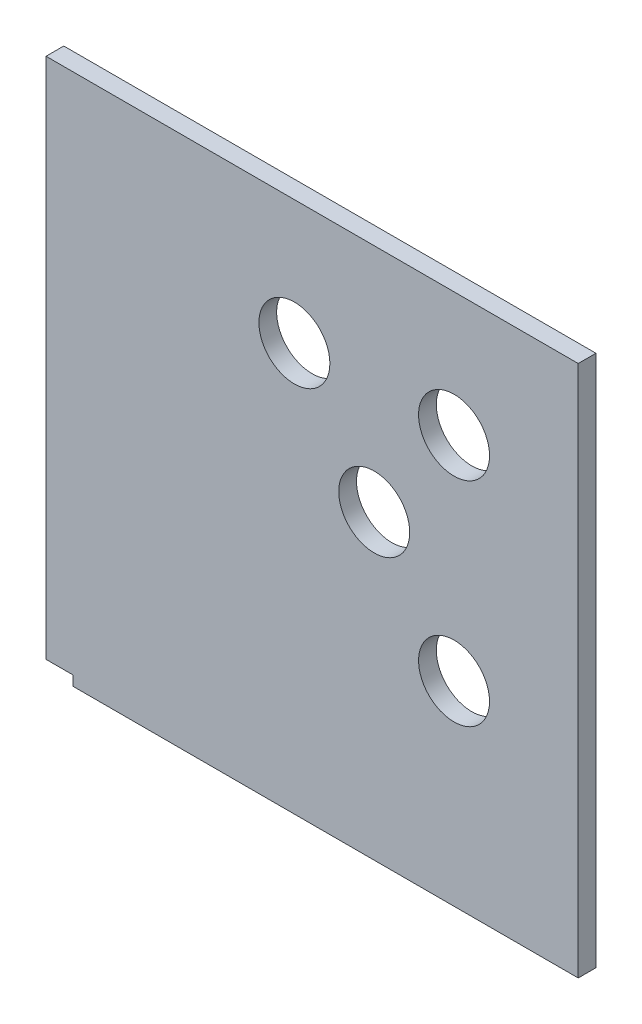
SolidWorks part; units mm, degrees
ref_plane "前视基准面" through (0, 0, 0) normal (0, 0, 1) x (1, 0, 0)
ref_plane "上视基准面" through (0, 0, 0) normal (0, 1, 0) x (1, 0, 0)
ref_plane "右视基准面" through (0, 0, 0) normal (1, 0, 0) x (0, 0, -1)
other "Configuration Table"
sketch "草图1" plane through (0, 0, 0) normal (0, 0, 1) x (1, 0, 0)
  line L1 (-150, -150) -> (150, -150)
  line L2 (-150, -150) -> (-150, 150)
  line L3 (-150, 150) -> (150, 150)
  line L4 (150, -150) -> (150, 150)
  line L5 (-150, -150) -> (150, 150) construction
  line L6 (-150, 150) -> (150, -150) construction
  point P0 (0, 0)
  dimension "D1" = 300
  dimension "D2" = 300
extrude "凸台-拉伸1" add sketch "草图1" along normal blind 10
sketch "草图2" plane through (0, 0, 10) normal (0, 0, 1) x (1, 0, 0)
  line L0 (-150, 150) -> (-150, -150) construction
  line L1 (-150, -150) -> (150, -150) construction
  circle A0 centre (-70, -70) radius 20
  circle A3 centre (35, 20) radius 20
  dimension "D3" = 40
  dimension "D4" = 90
  dimension "D10" = 40
  dimension "D1" = 80
  dimension "D2" = 80
  dimension "D5" = 105
extrude "切除-拉伸1" cut sketch "草图2" against normal through all contours A3
sketch "草图3" plane through (0, 0, 0) normal (0, 0, 1) x (1, 0, 0)
  line L4 (80, 80) -> (-10, 80) construction
  line L6 (-10, 80) -> (80, -40) construction
  circle A4 centre (80, 80) radius 20
  circle A5 centre (80, -40) radius 20
  circle A6 centre (-10, 80) radius 20
  circle A8 centre (35, 20) radius 20 construction
  circle A9 centre (35, 20) radius 20 construction
  point P6 (35, 20)
  dimension "D3" = 40
  dimension "D4" = 90
  dimension "D2" = 40
  dimension "D5" = 40
  dimension "D1" = 120
extrude "切除-拉伸2" cut sketch "草图3" along normal blind 10
sketch "草图4" plane through (0, 0, 10) normal (0, 0, 1) x (1, 0, 0)
  line L1 (-170.0688, -119.9497) -> (-134.6812, -119.9497)
  line L2 (-170.0688, -119.9497) -> (-170.0688, -155.3003)
  line L3 (-170.0688, -155.3003) -> (-134.6812, -155.3003)
  line L4 (-134.6812, -119.9497) -> (-134.6812, -155.3003)
  line L5 (-170.0688, -119.9497) -> (-134.6812, -155.3003) construction
  line L6 (-170.0688, -155.3003) -> (-134.6812, -119.9497) construction
  point P0 (-152.375, -137.625)
extrude "切除-拉伸3" cut sketch "草图4" against normal blind 25
sketch "草图5" plane through (0, -119.9497, 0) normal (0, -1, 0) x (1, 0, 0)
  line L4 (-150, 0) -> (-134.6812, 0)
  line L5 (-134.6812, 0) -> (-134.6812, 10)
  line L6 (-134.6812, 10) -> (-150, 10)
  line L7 (-150, 10) -> (-150, 0)
  line L8 (-150, 0) -> (-134.6812, 0)
  line L9 (-134.6812, 0) -> (-134.6812, 10)
  line L10 (-134.6812, 10) -> (-150, 10)
  line L11 (-150, 10) -> (-150, 0)
  dimension "D1" = 0
extrude "凸台-拉伸2" add sketch "草图5" along normal blind 24.5
